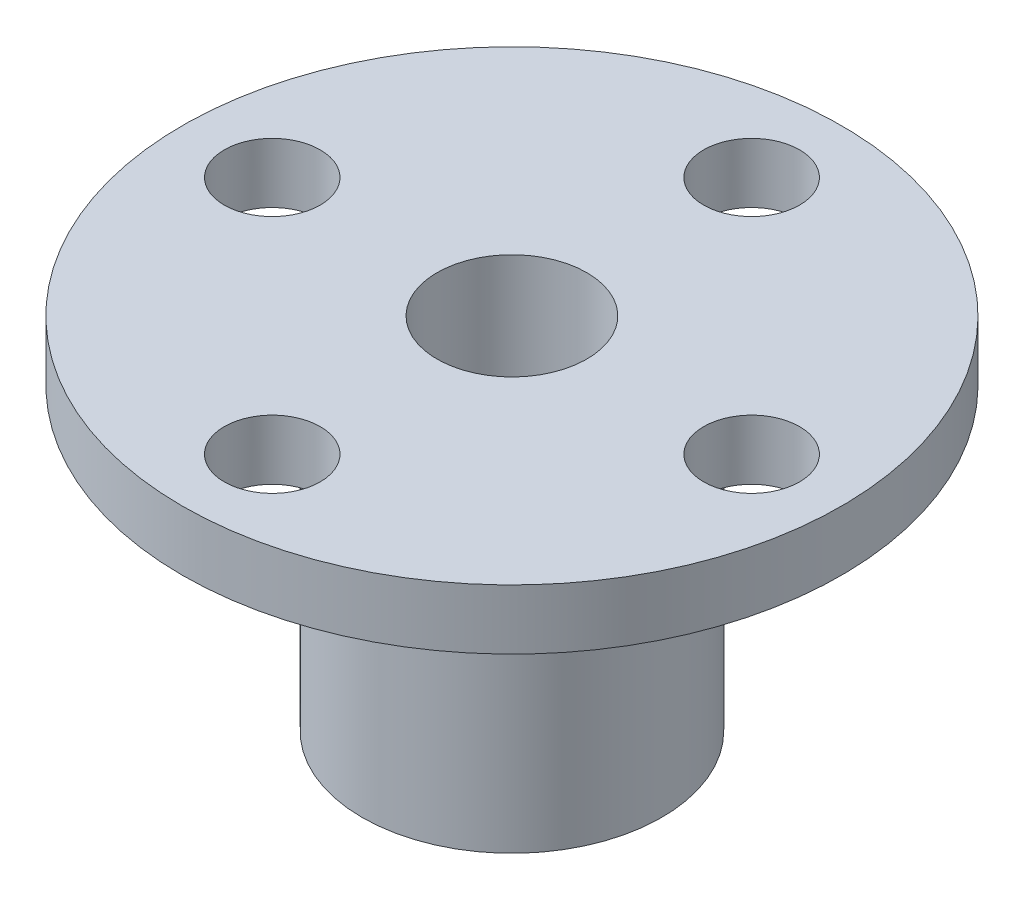
SolidWorks part; units mm, degrees
material "CA"
ref_plane "前视基准面" through (0, 0, 0) normal (0, 0, 1) x (1, 0, 0)
ref_plane "上视基准面" through (0, 0, 0) normal (0, 1, 0) x (1, 0, 0)
ref_plane "右视基准面" through (0, 0, 0) normal (1, 0, 0) x (0, 0, -1)
sketch "草图1" plane through (0, 0, 0) normal (0, 1, 0) x (1, 0, 0)
  circle A0 centre (0, 0) radius 5
  dimension "D1" = 10
extrude "凸台-拉伸1" add sketch "草图1" along normal blind 10
sketch "草图2" plane through (0, 10, 0) normal (0, 1, 0) x (1, 0, 0)
  circle A0 centre (0, 0) radius 11
  dimension "D1" = 22
extrude "凸台-拉伸2" add sketch "草图2" along normal blind 2
sketch "草图3" plane through (0, 0, 0) normal (0, -1, 0) x (1, 0, 0)
  circle A0 centre (0, 0) radius 2.5
  dimension "D1" = 5
extrude "切除-拉伸1" cut sketch "草图3" against normal through all
sketch "草图5" plane through (0, 10, 0) normal (0, -1, 0) x (-1, 0, 0)
  line L0 (-8, 0) -> (8, 0) construction
  circle A0 centre (0, 8) radius 1.6
  circle A2 centre (8, 0) radius 1.6
  circle A3 centre (0, -8) radius 1.6
  circle A4 centre (-8, 0) radius 1.6
  point P2 (0, 0)
  point P3 (-8, 0)
  point P4 (8, 0)
  point P14 (0, 0)
  dimension "D1" = 3.2
  dimension "D2" = 16
  dimension "D3" = 4
extrude "切除-拉伸3" cut sketch "草图5" against normal up to next
